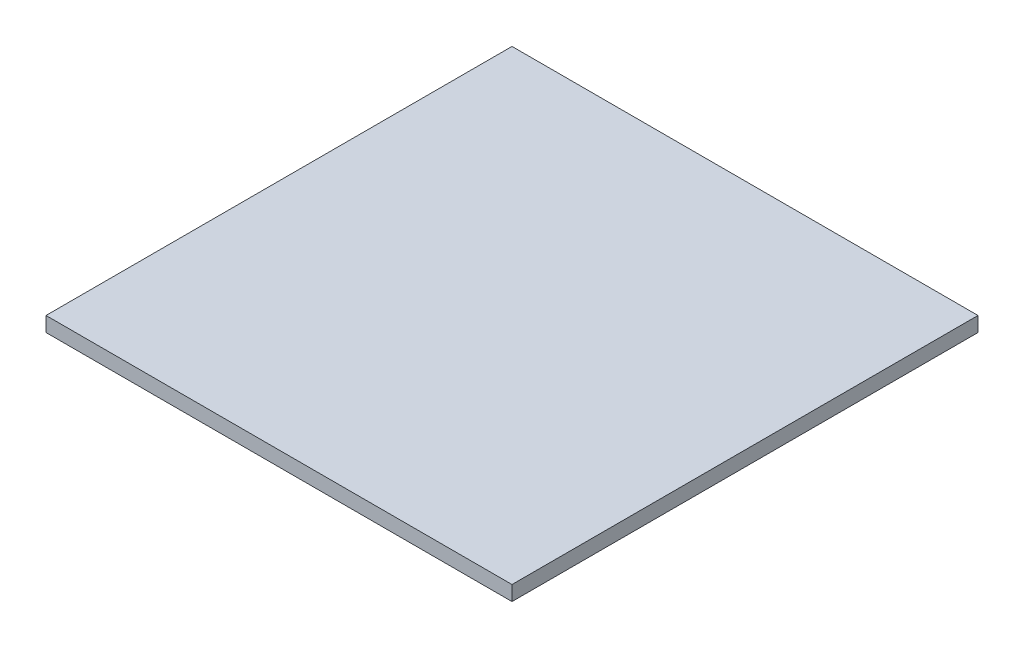
SolidWorks part; units mm, degrees
material "Acrylic (Medium-high impact)"
ref_plane "Front Plane" through (0, 0, 0) normal (0, 0, 1) x (1, 0, 0)
ref_plane "Top Plane" through (0, 0, 0) normal (0, 1, 0) x (1, 0, 0)
ref_plane "Right Plane" through (0, 0, 0) normal (1, 0, 0) x (0, 0, -1)
sketch "Sketch1" plane through (0, 0, 0) normal (0, 1, 0) x (1, 0, 0)
  line L1 (-50, -50) -> (50, -50)
  line L2 (-50, -50) -> (-50, 50)
  line L3 (-50, 50) -> (50, 50)
  line L4 (50, -50) -> (50, 50)
  line L5 (-50, -50) -> (50, 50) construction
  line L6 (-50, 50) -> (50, -50) construction
  point P0 (0, 0)
  dimension "D1" = 100
extrude "Boss-Extrude1" add sketch "Sketch1" along normal blind 3.175
